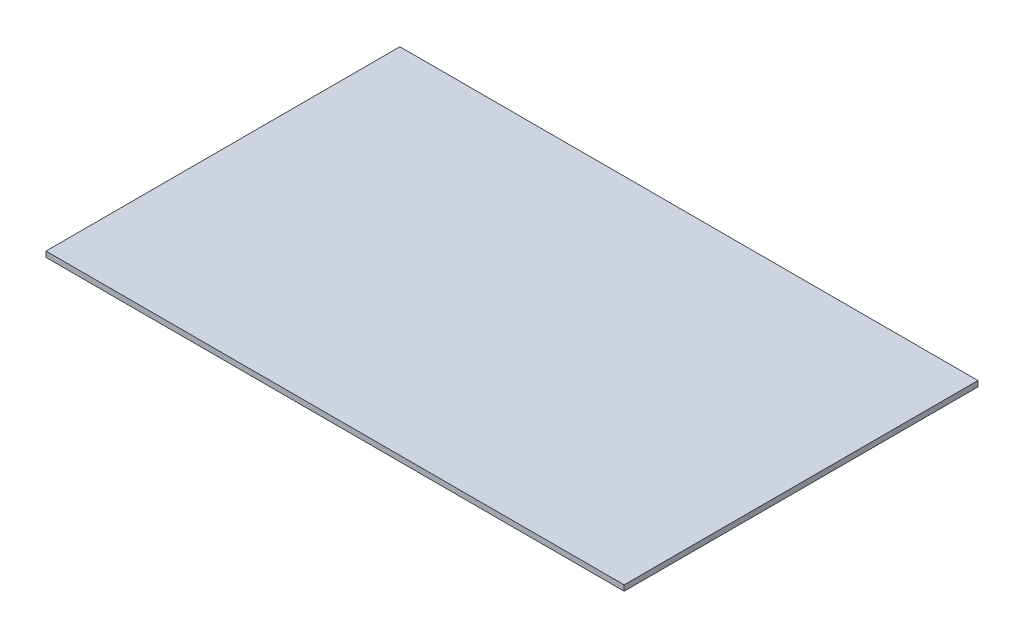
SolidWorks part; units mm, degrees
ref_plane "Front Plane" through (0, 0, 0) normal (0, 0, 1) x (1, 0, 0)
ref_plane "Top Plane" through (0, 0, 0) normal (0, 1, 0) x (1, 0, 0)
ref_plane "Right Plane" through (0, 0, 0) normal (1, 0, 0) x (0, 0, -1)
sketch "Sketch1" plane through (0, 0, 0) normal (0, 1, 0) x (1, 0, 0)
  line L1 (-156.466, 95.7728) -> (156.466, 95.7728)
  line L2 (-156.466, 95.7728) -> (-156.466, -95.7728)
  line L3 (-156.466, -95.7728) -> (156.466, -95.7728)
  line L4 (156.466, 95.7728) -> (156.466, -95.7728)
  line L5 (-156.466, 95.7728) -> (156.466, -95.7728) construction
  line L6 (-156.466, -95.7728) -> (156.466, 95.7728) construction
  point P0 (0, 0)
extrude "Boss-Extrude1" add sketch "Sketch1" along normal blind 3 contours L1 L4 L3 L2
sketch "Sketch2" plane through (0, 3, 0) normal (0, 1, 0) x (1, 0, 0)
  line L0 (24.094, -65.8361) -> (76.751, 0)
